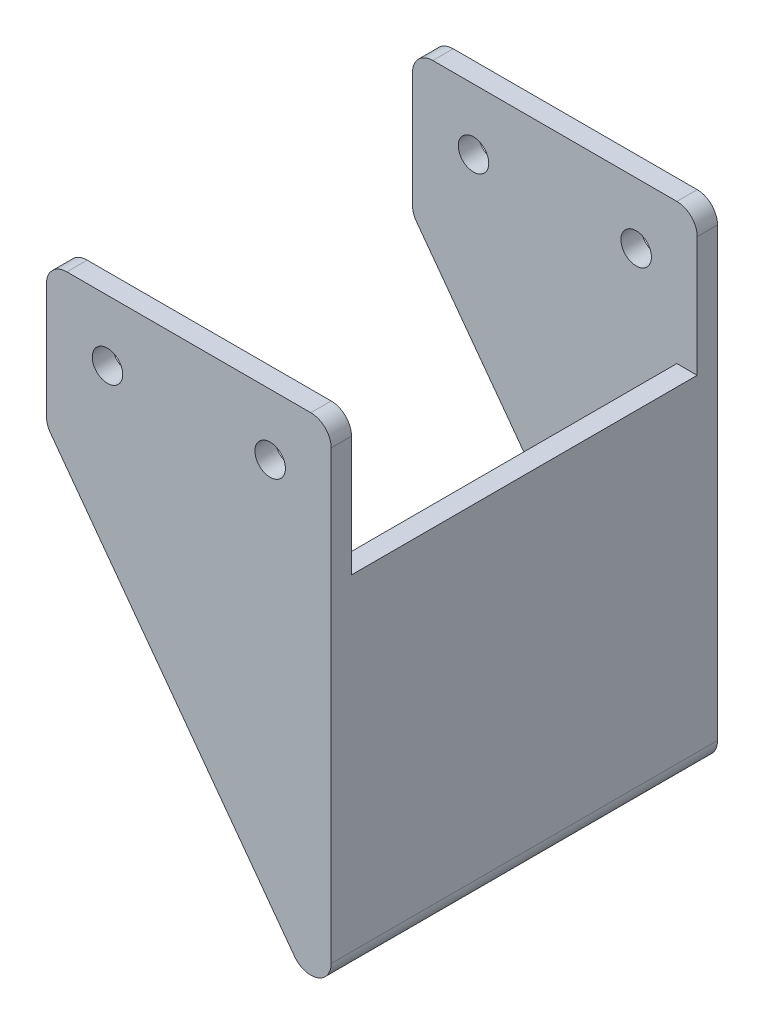
SolidWorks part; units mm, degrees
ref_plane "Front Plane" through (0, 0, 0) normal (0, 0, 1) x (1, 0, 0)
ref_plane "Top Plane" through (0, 0, 0) normal (0, 1, 0) x (1, 0, 0)
ref_plane "Right Plane" through (0, 0, 0) normal (1, 0, 0) x (0, 0, -1)
sketch "Sketch1" plane through (0, 0, 0) normal (0, 0, 1) x (1, 0, 0)
  line L0 (0, -1) -> (0, -22.9571)
  line L1 (-1.8051, -23.5503) -> (-13.8051, -7.2646)
  line L2 (-14, -6.6714) -> (-14, -1)
  line L3 (-13, 0) -> (-1, 0)
  arc A0 (0, -22.9571) -> (-1.8051, -23.5503) centre (-1, -22.9571) cw
  arc A1 (-13.8051, -7.2646) -> (-14, -6.6714) centre (-13, -6.6714) cw
  arc A2 (-14, -1) -> (-13, 0) centre (-13, -1) cw
  arc A3 (0, -1) -> (-1, 0) centre (-1, -1) ccw
  circle A4 centre (-11, -3) radius 0.75
  circle A5 centre (-3, -3) radius 0.75
  point P7 (0, -26)
  point P10 (-14, -7)
  point P13 (-14, 0)
  point P16 (0, 0)
  dimension "D4" = 1
  dimension "D5" = 1
  dimension "D6" = 8
  dimension "D8" = 1.5
  dimension "D9" = 1.5
  dimension "D1" = 26
  dimension "D2" = 14
  dimension "D3" = 7
  dimension "D7" = 3
  dimension "D10" = 3
extrude "Boss-Extrude1" add sketch "Sketch1" along normal mid plane 19
sketch "Sketch2" plane through (0, 0, 0) normal (0, 0, 1) x (1, 0, 0)
  line L0 (-1, -28.3486) -> (-1, -6.9071)
  line L1 (-1, -6.9071) -> (7.9264, -6.9071)
  line L2 (7.9264, -6.9071) -> (7.2949, 4.747)
  line L3 (7.2949, 4.747) -> (-21.6673, 6.8711)
  line L4 (-21.6673, 6.8711) -> (-20.0347, -23.2588)
  line L5 (-20.0347, -23.2588) -> (-1, -28.3486)
  line L6 (0, -22.9571) -> (0, -1) construction
  arc A0 (-1.8051, -23.5503) -> (0, -22.9571) centre (-1, -22.9571) ccw construction
  point P9 (-0.6878, -23.9071)
  dimension "D1" = 17
  dimension "D2" = 1
extrude "Cut-Extrude1" cut sketch "Sketch2" against normal mid plane 17
